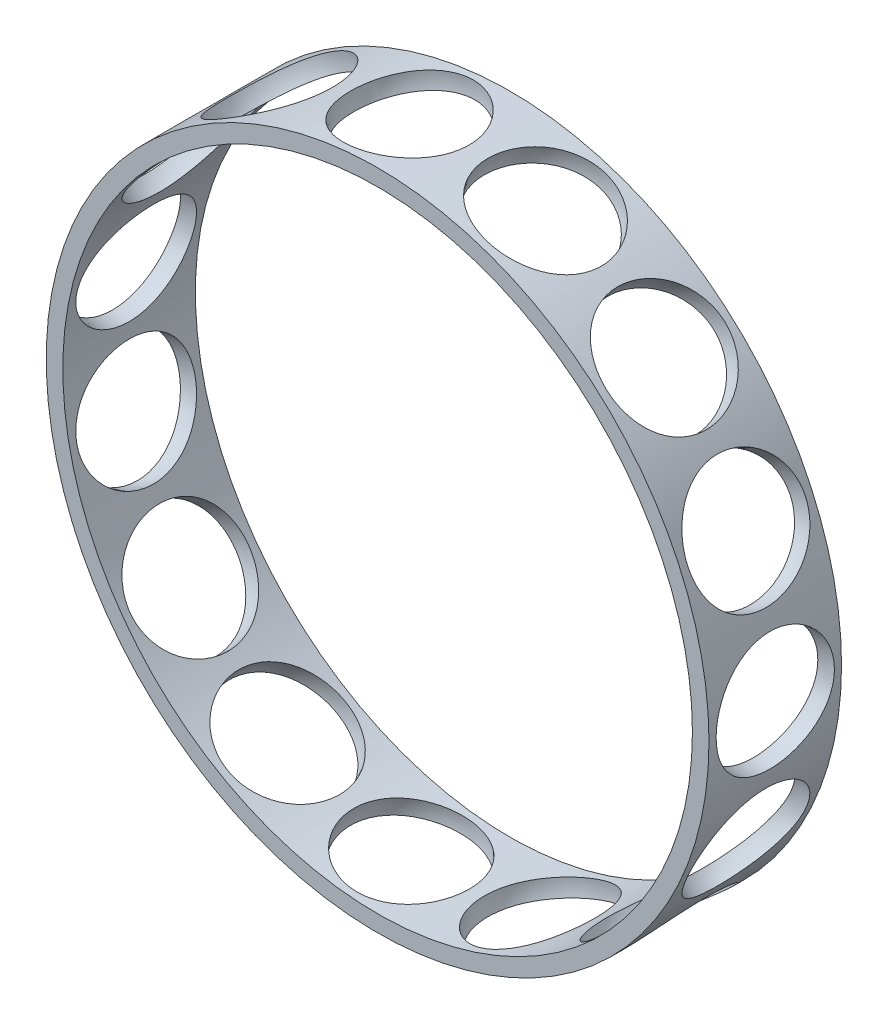
SolidWorks part; units mm, degrees
ref_plane "前视基准面" through (0, 0, 0) normal (0, 0, 1) x (1, 0, 0)
ref_plane "上视基准面" through (0, 0, 0) normal (0, 1, 0) x (1, 0, 0)
ref_plane "右视基准面" through (0, 0, 0) normal (1, 0, 0) x (0, 0, -1)
other "Configuration Table"
sketch "草图1" plane through (0, 0, 0) normal (0, 0, 1) x (1, 0, 0)
  circle A0 centre (0, 0) radius 50
  circle A1 centre (0, 0) radius 47.5
  dimension "D1" = 95
  dimension "D2" = 100
extrude "凸台-拉伸1" add sketch "草图1" along normal mid plane 20
sketch "草图2" plane through (0, 0, 0) normal (0, 1, 0) x (1, 0, 0)
  line L1 (48.75, 9) -> (48.75, -9)
  arc A0 (48.75, -9) -> (48.75, 9) centre (48.75, 0) ccw
  point P1 (50, 0)
  point P2 (0, 0)
  point P6 (0, 0)
  dimension "D1" = 18
  dimension "D2" = 48.75
revolve "切除-旋转1" cut sketch "草图2" angle 360 about L1
pattern_circular "阵列(圆周)1" count 15 over 360 about axis through (0, 0, 0) along (0, 0, 1) of "切除-旋转1"
